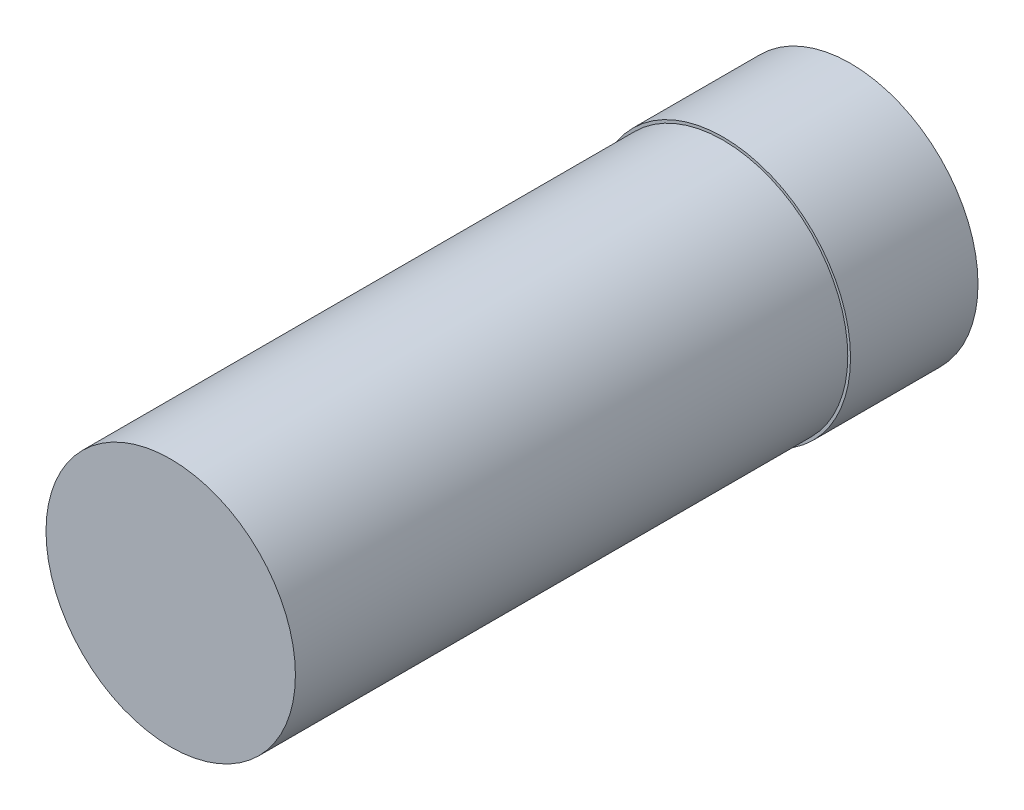
SolidWorks part; units mm, degrees
ref_plane "정면" through (0, 0, 0) normal (0, 0, 1) x (1, 0, 0)
ref_plane "윗면" through (0, 0, 0) normal (0, 1, 0) x (1, 0, 0)
ref_plane "우측면" through (0, 0, 0) normal (1, 0, 0) x (0, 0, -1)
sketch "스케치1" plane through (0, 0, 0) normal (0, 0, 1) x (1, 0, 0)
  circle A0 centre (0, 0) radius 3
  dimension "D1" = 6
extrude "보스-돌출1" add sketch "스케치1" along normal blind 3
sketch "스케치2" plane through (0, 0, 3) normal (0, 0, 1) x (1, 0, 0)
  circle A0 centre (0, 0) radius 2.935
  dimension "D1" = 5.87
extrude "보스-돌출2" add sketch "스케치2" along normal blind 13
sketch "스케치3" plane through (0, 0, 16) normal (0, 0, 1) x (1, 0, 0)
  circle A0 centre (0, 0) radius 2.45
  dimension "D1" = 4.9
